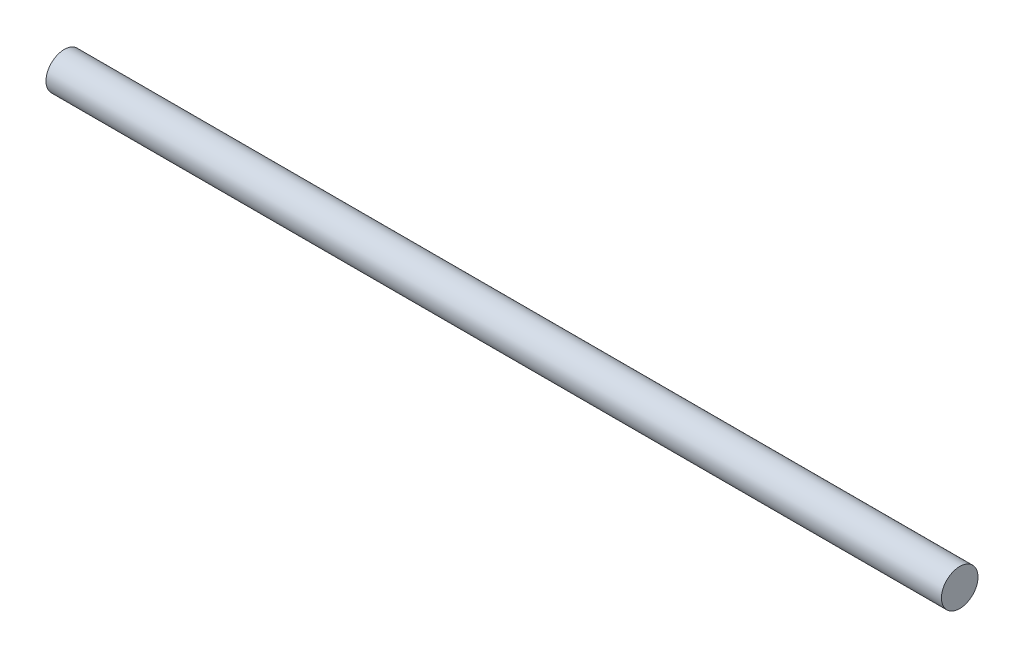
SolidWorks part; units mm, degrees
material "Zoltek Panex 33"
ref_plane "Front Plane" through (0, 0, 0) normal (0, 0, 1) x (1, 0, 0)
ref_plane "Top Plane" through (0, 0, 0) normal (0, 1, 0) x (1, 0, 0)
ref_plane "Right Plane" through (0, 0, 0) normal (1, 0, 0) x (0, 0, -1)
sketch "Sketch1" plane through (0, 0, 0) normal (1, 0, 0) x (0, 0, -1)
  circle A0 centre (0, 0) radius 9
  dimension "D1" = 18
extrude "Boss-Extrude1" add sketch "Sketch1" along normal mid plane 441
